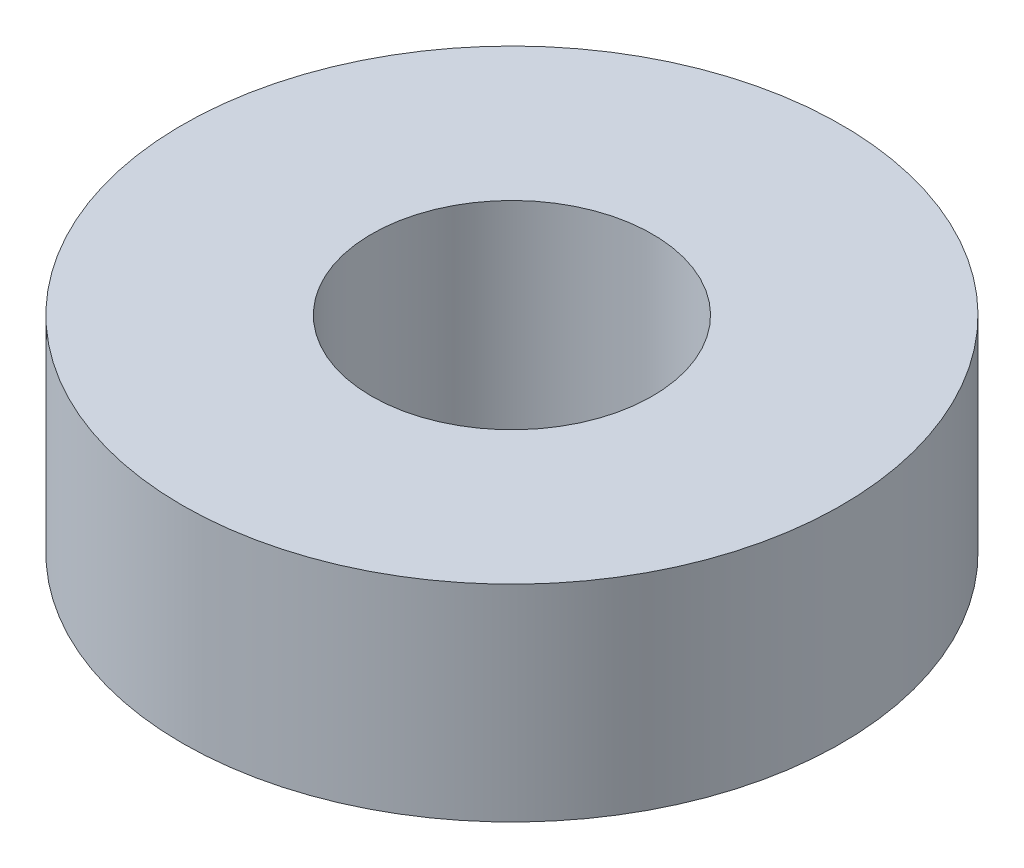
SolidWorks part; units mm, degrees
ref_plane "Płaszczyzna przednia" through (0, 0, 0) normal (0, 0, 1) x (1, 0, 0)
ref_plane "Płaszczyzna górna" through (0, 0, 0) normal (0, 1, 0) x (1, 0, 0)
ref_plane "Płaszczyzna prawa" through (0, 0, 0) normal (1, 0, 0) x (0, 0, -1)
sketch "Sketch1" plane through (0, 0, 0) normal (0, 1, 0) x (1, 0, 0)
  circle A0 centre (0, 0) radius 7.5
  circle A1 centre (0, 0) radius 17.6
  dimension "D1" = 15
  dimension "D2" = 35.2
extrude "Boss-Extrude1" add sketch "Sketch1" along normal blind 11
